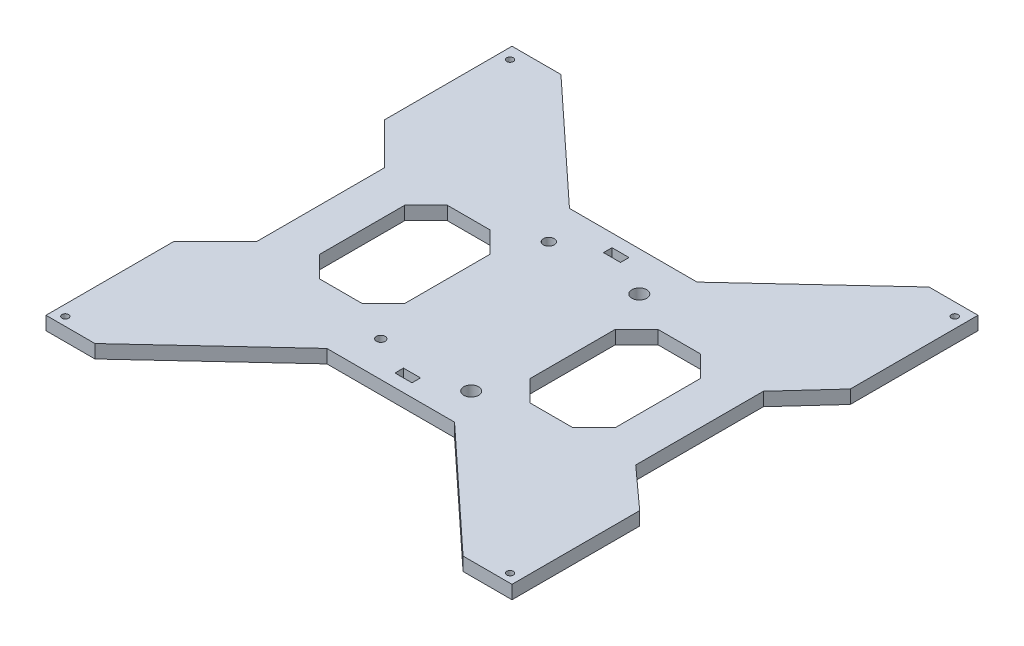
SolidWorks part; units mm, degrees
ref_plane "Front Plane" through (0, 0, 0) normal (0, 0, 1) x (1, 0, 0)
ref_plane "Top Plane" through (0, 0, 0) normal (0, 1, 0) x (1, 0, 0)
ref_plane "Right Plane" through (0, 0, 0) normal (1, 0, 0) x (0, 0, -1)
sketch "Sketch1" plane through (0, 0, 0) normal (0, 1, 0) x (1, 0, 0)
  line L0 (19.5, 109.5) -> (199.5, 109.5) construction
  line L1 (0, 0) -> (23, 0)
  line L2 (0, 0) -> (0, 60)
  line L3 (0, 219) -> (23, 219)
  line L4 (219, 0) -> (219, 60)
  line L5 (79.5, 166.5) -> (139.5, 166.5)
  line L6 (19.5, 139.5) -> (19.5, 79.5)
  line L7 (79.5, 52.5) -> (139.5, 52.5)
  line L8 (199.5, 137.6424) -> (199.5, 77.6424)
  line L9 (79.5, 166.5) -> (23, 219)
  line L10 (109.5, 166.5) -> (109.5, 52.5) construction
  line L11 (139.5, 166.5) -> (196, 219)
  line L12 (79.5, 52.5) -> (23, 0)
  line L13 (139.5, 52.5) -> (196, 0)
  line L14 (19.5, 139.5) -> (0, 159)
  line L15 (19.5, 79.5) -> (0, 60)
  line L16 (199.5, 137.6424) -> (219, 159)
  line L17 (199.5, 77.6424) -> (219, 60)
  line L18 (196, 219) -> (219, 219)
  line L19 (196, 0) -> (219, 0)
  line L20 (0, 159) -> (0, 219)
  line L21 (219, 159) -> (219, 219)
  dimension "D1" = 219
  dimension "D2" = 219
  dimension "D3" = 19.5
  dimension "D4" = 52.5
  dimension "D5" = 19.5
  dimension "D6" = 52.5
  dimension "D7" = 60
  dimension "D8" = 109.5
  dimension "D9" = 109.5
  dimension "D10" = 60
  dimension "D11" = 60
  dimension "D12" = 60
  dimension "D13" = 60
  dimension "D14" = 60
  dimension "D15" = 60
  dimension "D16" = 60
  dimension "D17" = 23
  dimension "D18" = 23
  dimension "D19" = 23
  dimension "D20" = 23
extrude "Boss-Extrude1" add sketch "Sketch1" along normal blind 6.3 contours L8 L5 L6 L7 | L20 L14 L6 L5 L9 L3 | L6 L15 L2 L1 L12 L7 | L13 L19 L4 L17 L8 L7 | L16 L21 L18 L11 L5 L8
sketch "Sketch3" plane through (0, 6.3, 0) normal (0, 1, 0) x (1, 0, 0)
  line L1 (113.5, 160.5) -> (105.5, 160.5)
  line L2 (113.5, 160.5) -> (113.5, 156.5)
  line L3 (113.5, 156.5) -> (105.5, 156.5)
  line L4 (105.5, 160.5) -> (105.5, 156.5)
  line L5 (105.5, 62.5) -> (113.5, 62.5)
  line L6 (105.5, 62.5) -> (105.5, 58.5)
  line L7 (105.5, 58.5) -> (113.5, 58.5)
  line L8 (113.5, 62.5) -> (113.5, 58.5)
  line L16 (105.5, 160.5) -> (113.5, 156.5) construction
  line L17 (113.5, 160.5) -> (105.5, 156.5) construction
  line L18 (105.5, 62.5) -> (113.5, 58.5) construction
  line L19 (113.5, 62.5) -> (105.5, 58.5) construction
  line L20 (79.5, 166.5) -> (139.5, 166.5) construction
  line L22 (109.5, 166.5) -> (109.5, 52.5) construction
  line L23 (79.5, 52.5) -> (139.5, 52.5) construction
  line L25 (19.5, 139.5) -> (19.5, 79.5) construction
  line L26 (19.5, 109.5) -> (199.5, 107.6424) construction
  line L27 (199.5, 137.6424) -> (199.5, 77.6424) construction
  line L28 (39.5, 79.0872) -> (79.5, 79.0872)
  line L29 (39.5, 79.0872) -> (39.5, 139.0872)
  line L30 (39.5, 139.0872) -> (79.5, 139.0872)
  line L31 (79.5, 79.0872) -> (79.5, 139.0872)
  line L32 (39.5, 79.0872) -> (79.5, 139.0872) construction
  line L33 (39.5, 139.0872) -> (79.5, 79.0872) construction
  line L34 (139.5, 78.0552) -> (179.5, 78.0552)
  line L35 (139.5, 78.0552) -> (139.5, 138.0552)
  line L36 (139.5, 138.0552) -> (179.5, 138.0552)
  line L37 (179.5, 78.0552) -> (179.5, 138.0552)
  line L38 (139.5, 78.0552) -> (179.5, 138.0552) construction
  line L39 (139.5, 138.0552) -> (179.5, 78.0552) construction
  point P8 (59.5, 109.0872)
  point P13 (159.5, 108.0552)
  point P28 (109.5, 160.5)
  point P29 (109.5, 60.5)
  dimension "D1" = 6
  dimension "D2" = 4
  dimension "D3" = 8
  dimension "D4" = 6
  dimension "D5" = 8
  dimension "D6" = 4
  dimension "D7" = 20
  dimension "D8" = 20
  dimension "D9" = 40
  dimension "D10" = 40
  dimension "D11" = 60
  dimension "D12" = 60
extrude "Cut-Extrude1" cut sketch "Sketch3" against normal through all
chamfer "Chamfer1" distance 10 8 edges at (79.5, 3.15, -79.0872) (179.5, 3.15, -78.0552) (139.5, 3.15, -78.0552) (39.5, 3.15, -79.0872) (139.5, 3.15, -138.0552) (179.5, 3.15, -138.0552) (79.5, 3.15, -139.0872) (39.5, 3.15, -139.0872)
sketch "Sketch4" plane through (0, 6.3, 0) normal (0, 1, 0) x (1, 0, 0)
  line L0 (109.5, 166.5) -> (109.5, 52.5) construction
  line L1 (79.5, 166.5) -> (139.5, 166.5) construction
  line L2 (79.5, 52.5) -> (139.5, 52.5) construction
  line L3 (88.25, 148.0712) -> (130.75, 69.0712) construction
  line L4 (19.5, 139.5) -> (19.5, 79.5) construction
  line L5 (19.5, 109.5) -> (199.5, 107.6424) construction
  line L6 (199.5, 137.6424) -> (199.5, 77.6424) construction
  line L7 (5, 4.0712) -> (214, 4.0712) construction
  line L8 (5, 4.0712) -> (5, 213.0712) construction
  line L9 (5, 213.0712) -> (214, 213.0712) construction
  line L10 (214, 4.0712) -> (214, 213.0712) construction
  line L11 (5, 4.0712) -> (214, 213.0712) construction
  line L12 (5, 213.0712) -> (214, 4.0712) construction
  line L13 (88.25, 148.0712) -> (130.75, 148.0712) construction
  line L14 (88.25, 148.0712) -> (88.25, 69.0712) construction
  line L15 (88.25, 69.0712) -> (130.75, 69.0712) construction
  line L16 (130.75, 148.0712) -> (130.75, 69.0712) construction
  circle A0 centre (5, 213.0712) radius 1.55
  circle A1 centre (214, 213.0712) radius 1.55
  circle A2 centre (214, 4.0712) radius 1.55
  circle A3 centre (5, 4.0712) radius 1.55
  circle A4 centre (88.25, 148.0712) radius 2.55
  circle A5 centre (88.25, 69.0712) radius 2.05
  circle A6 centre (130.75, 69.0712) radius 3.5
  circle A7 centre (130.75, 148.0712) radius 3.5
  point P9 (109.5, 108.5712)
  point P29 (109.5, 108.5712)
  dimension "D3" = 3.1
  dimension "D4" = 3.1
  dimension "D5" = 3.1
  dimension "D6" = 3.1
  dimension "D7" = 42.5
  dimension "D9" = 5.1
  dimension "D10" = 7
  dimension "D11" = 4.1
  dimension "D12" = 7
  dimension "D1" = 209
  dimension "D2" = 209
  dimension "D8" = 79
extrude "Cut-Extrude2" cut sketch "Sketch4" against normal through all
